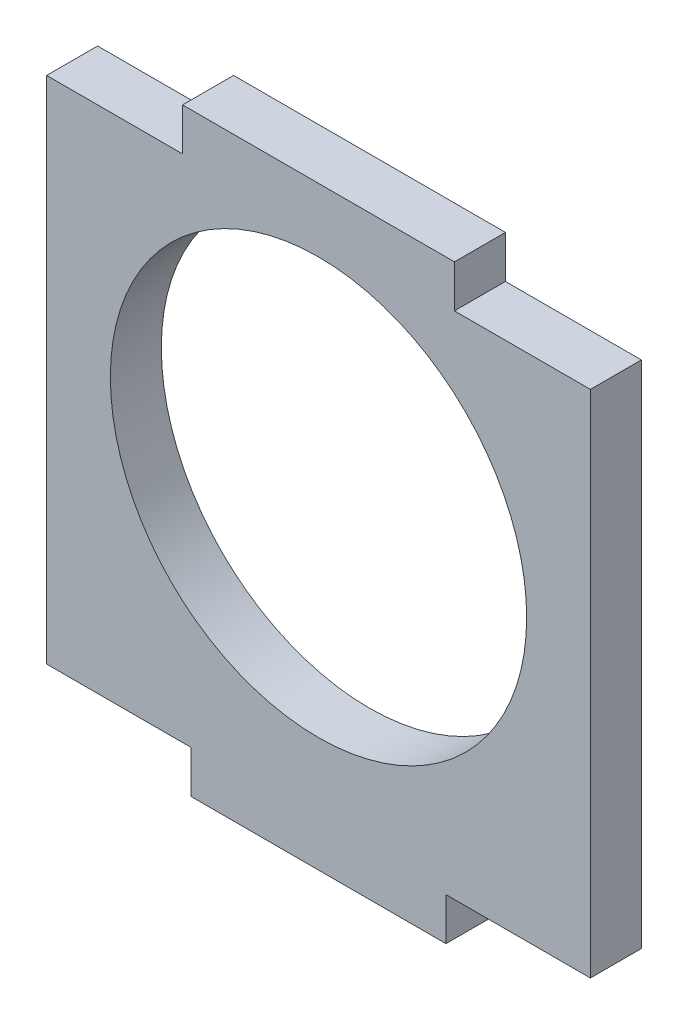
SolidWorks part; units mm, degrees
ref_plane "Plan de face" through (0, 0, 0) normal (0, 0, 1) x (1, 0, 0)
ref_plane "Plan de dessus" through (0, 0, 0) normal (0, 1, 0) x (1, 0, 0)
ref_plane "Plan de droite" through (0, 0, 0) normal (1, 0, 0) x (0, 0, -1)
sketch "Esquisse1" plane through (0, 0, 0) normal (0, 0, 1) x (1, 0, 0)
  line L0 (-16, 15) -> (-8, 15)
  line L1 (-8, 17.5) -> (-8, 15)
  line L2 (-8, 17.5) -> (8, 17.5)
  line L3 (8, 17.5) -> (8, 15)
  line L4 (8, 15) -> (16, 15)
  line L6 (16, -15) -> (7.5, -15)
  line L7 (7.5, -17.5) -> (-7.5, -17.5)
  line L8 (-7.5, -15) -> (-16, -15)
  line L9 (-16, -15) -> (-16, 15)
  line L10 (-7.5, -17.5) -> (-7.5, -15)
  line L11 (7.5, -17.5) -> (7.5, -15)
  line L12 (16, 15) -> (16, -15)
  circle A0 centre (0, 1.5) radius 12.25
  dimension "D1" = 24.5
  dimension "D11" = 16
  dimension "D2" = 1.5
  dimension "D3" = 32
  dimension "D4" = 16
  dimension "D5" = 17.5
  dimension "D6" = 35
  dimension "D7" = 15
  dimension "D8" = 30
  dimension "D9" = 15
  dimension "D10" = 7.5
  dimension "D12" = 8
extrude "Boss.-Extru.1" add sketch "Esquisse1" along normal blind 3
